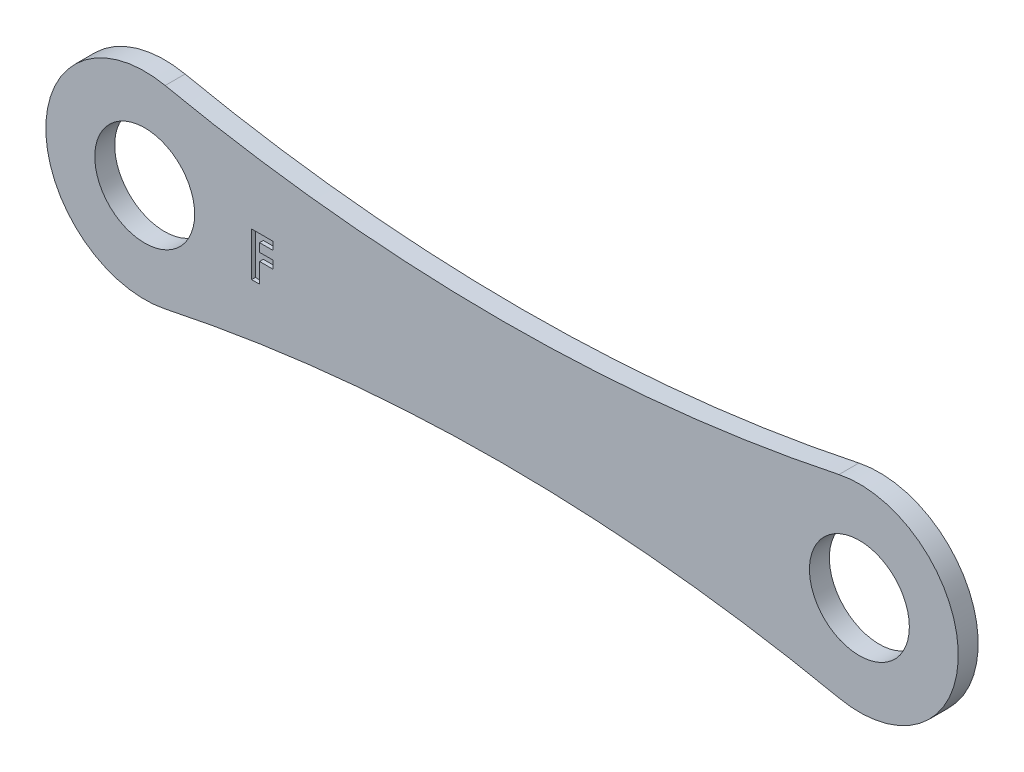
SolidWorks part; units mm, degrees
ref_plane "Plan de face" through (0, 0, 0) normal (1, 0, 0) x (0, 1, 0)
ref_plane "Plan de dessus" through (0, 0, 0) normal (0, 0, 1) x (0, 1, 0)
ref_plane "Plan de droite" through (0, 0, 0) normal (0, 1, 0) x (-1, 0, 0)
sketch "Esquisse1" plane through (0, 0, 0) normal (0, 0, 1) x (0, 1, 0)
  line L0 (0, 57.02) -> (0, 0) construction
  circle A0 centre (0, 0) radius 3.985
  circle A1 centre (0, 57.02) radius 3.985
  circle A2 centre (0, 57.02) radius 7.89
  circle A3 centre (0, 0) radius 7.89
  arc A4 (7.7195, 1.6313) -> (7.7195, 55.3887) centre (134.9105, 28.51) cw
  arc A5 (-7.7195, 1.6313) -> (-7.7195, 55.3887) centre (-134.9105, 28.51) ccw
  dimension "D2" = 7.97
  dimension "D3" = 15.78
  dimension "D4" = 130
  dimension "D1" = 57.02
extrude "Boss.-Extru.1" add sketch "Esquisse1" along normal blind 1.588
sketch "Esquisse2" plane through (0, 0, 1.588) normal (0, 0, 1) x (1, 0, 0)
  text T0 "<b>F</b>"
extrude "Enlèv. mat.-Extru.1" cut sketch "Esquisse2" against normal blind 0.3
